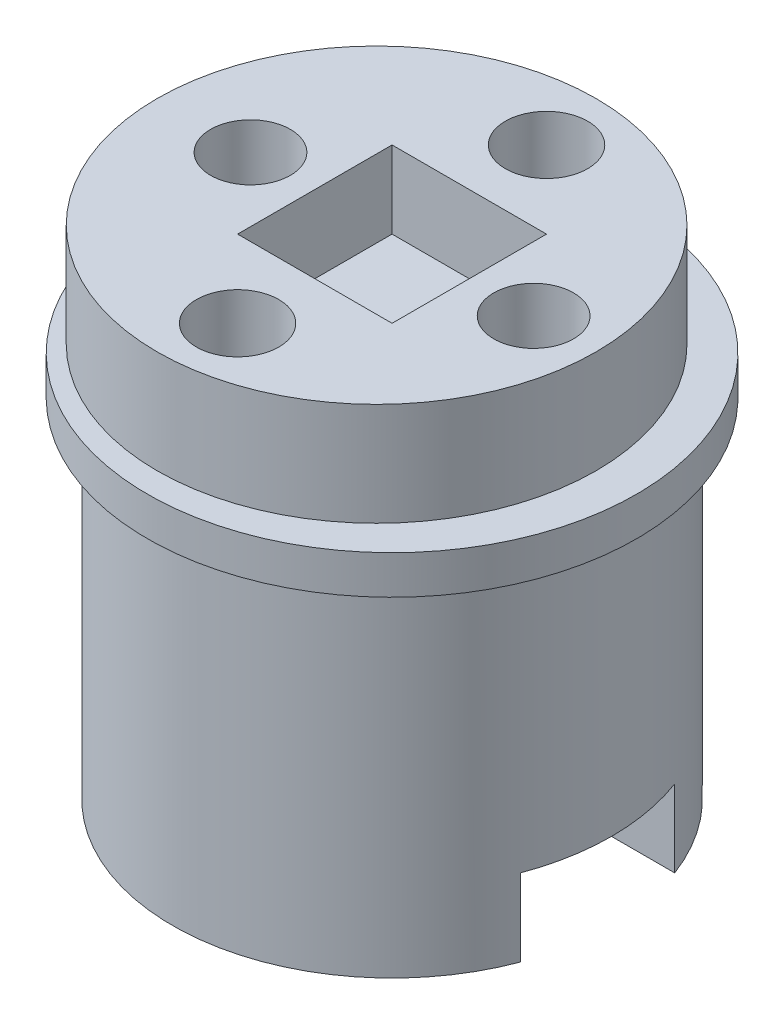
SolidWorks part; units mm, degrees
material "Like ABS"
ref_plane "Front Plane" through (0, 0, 0) normal (0, 0, 1) x (1, 0, 0)
ref_plane "Top Plane" through (0, 0, 0) normal (0, 1, 0) x (1, 0, 0)
ref_plane "Right Plane" through (0, 0, 0) normal (1, 0, 0) x (0, 0, -1)
sketch "Sketch1" plane through (0, 0, 0) normal (0, 1, 0) x (1, 0, 0)
  circle A0 centre (0, 0) radius 8.525
  dimension "D1" = 17.05
extrude "Boss-Extrude11" add sketch "Sketch1" along normal blind 4
sketch "Sketch20" plane through (0, 4, 0) normal (0, 1, 0) x (1, 0, 0)
  line L0 (0, 0) -> (1.2, 0) construction
  circle A0 centre (1.2, 0) radius 8.575
  dimension "D2" = 17.15
  dimension "D1" = 1.2
extrude "Boss-Extrude12" add sketch "Sketch20" along normal blind 4
sketch "Sketch21" plane through (0, 8, 0) normal (0, 1, 0) x (1, 0, 0)
  line L0 (0, 0) -> (0.6, 0) construction
  circle A0 centre (0.6, 0) radius 9.5
  dimension "D2" = 19
  dimension "D1" = 0.6
extrude "Boss-Extrude13" add sketch "Sketch21" along normal blind 1.25
sketch "Sketch22" plane through (0, 9.25, 0) normal (0, 1, 0) x (1, 0, 0)
  line L0 (0, 0) -> (0.6, 0) construction
  circle A0 centre (0.6, 0) radius 8.55
  dimension "D2" = 17.1
  dimension "D1" = 0.6
extrude "Boss-Extrude14" add sketch "Sketch22" along normal blind 7
sketch "Sketch30" plane through (0, 0, 0) normal (0, -1, 0) x (1, 0, 0)
  line L0 (0, 0) -> (0.6, 0) construction
  circle A1 centre (0.6, 0) radius 8.525
  dimension "D1" = 0.6
  dimension "D2" = 17.05
extrude "Boss-Extrude15" add sketch "Sketch30" along normal blind 15
sketch "Sketch33" plane through (0, -15, 0) normal (0, -1, 0) x (1, 0, 0)
  line L0 (0, 0) -> (0.6, 0) construction
  circle A0 centre (0.6, 0) radius 2.1
  dimension "D2" = 4.2
  dimension "D1" = 0.6
extrude "Cut-Extrude14" cut sketch "Sketch33" against normal blind 5.8
sketch "Sketch35" plane through (0, 0, 0) normal (0, -1, 0) x (1, 0, 0)
  line L0 (0, 0) -> (0.6, 0) construction
  circle A0 centre (0.6, 0) radius 9.5
  dimension "D2" = 19
  dimension "D1" = 0.6
extrude "Boss-Extrude16" add sketch "Sketch35" along normal blind 1.5
sketch "Sketch36" plane through (0, -15, 0) normal (0, -1, 0) x (1, 0, 0)
  circle A0 centre (0.6, 0) radius 6 construction
  circle A1 centre (0.6, 6) radius 1.6
  dimension "D1" = 12
  dimension "D2" = 3.2
extrude "Cut-Extrude15" cut sketch "Sketch36" against normal up to surface (31.25 mm away) up to face at (0.6, 16.25, 8.55)
pattern_circular "CirPattern1" count 2 over 360 about axis through (0.6, 0, 0) along (0, 1, 0) of "Cut-Extrude15"
sketch "Sketch43" plane through (0, -15, 0) normal (0, -1, 0) x (1, 0, 0)
  circle A1 centre (-4.9, 0) radius 1.55
  circle A2 centre (6.1, 0) radius 1.55
  circle A3 centre (0.6, 0) radius 5.5 construction
  dimension "D1" = 11
  dimension "D2" = 3.1
extrude "Cut-Extrude20" cut sketch "Sketch43" against normal up to surface (31.25 mm away) up to face at (0.6, 16.25, -4.4)
sketch "Sketch44" plane through (0, 16.25, 0) normal (0, 1, 0) x (1, 0, 0)
  circle A0 centre (-4.9, 0) radius 2
  circle A1 centre (6.1, 0) radius 2
  dimension "D1" = 4
extrude "Cut-Extrude21" cut sketch "Sketch44" against normal blind 4
sketch "Sketch45" plane through (0, 16.25, 0) normal (0, 1, 0) x (1, 0, 0)
  line L2 (-2.4, -6) -> (-2.4, -10.8726)
  line L3 (-2.4, -10.8726) -> (3.6, -10.8726)
  line L4 (3.6, -6) -> (3.6, -10.8726)
  line L6 (-2.4, 6) -> (-2.4, 11.4221)
  line L7 (-2.4, 11.4221) -> (3.6, 11.4221)
  line L8 (3.6, 6) -> (3.6, 11.4221)
  arc A0 (-2.4, 6) -> (3.6, 6) centre (0.6, 6) ccw
  arc A1 (3.6, -6) -> (-2.4, -6) centre (0.6, -6) ccw
  dimension "D1" = 6
  dimension "D2" = 6
extrude "Cut-Extrude22" cut sketch "Sketch45" against normal blind 3
sketch "Sketch46" plane through (0, -15, 0) normal (0, -1, 0) x (1, 0, 0)
  line L1 (-4.9, 3) -> (-9.7199, 3)
  line L3 (-4.9, -3) -> (-9.7199, -3)
  line L4 (-9.7199, 3) -> (-9.7199, -3)
  line L5 (6.1, 3) -> (10.8894, 3)
  line L7 (6.1, -3) -> (10.8894, -3)
  line L8 (10.8894, 3) -> (10.8894, -3)
  arc A0 (-4.9, -3) -> (-4.9, 3) centre (-4.9, 0) ccw
  arc A1 (6.1, 3) -> (6.1, -3) centre (6.1, 0) ccw
  dimension "D1" = 6
extrude "Cut-Extrude23" cut sketch "Sketch46" against normal blind 3
sketch "Sketch47" plane through (0, 16.25, 0) normal (0, 1, 0) x (1, 0, 0)
  line L1 (-10.7961, 10.8817) -> (11.5477, 10.8817)
  line L2 (-10.7961, 10.8817) -> (-10.7961, -10.9081)
  line L3 (-10.7961, -10.9081) -> (11.5477, -10.9081)
  line L4 (11.5477, 10.8817) -> (11.5477, -10.9081)
extrude "Cut-Extrude24" cut sketch "Sketch47" against normal up to surface (12.25 mm away) up to face at (-7.95, 4, 0)
sketch "Sketch48" plane through (0, 4, 0) normal (0, 1, 0) x (1, 0, 0)
  line L1 (3.6, 3) -> (-2.4, 3)
  line L2 (3.6, 3) -> (3.6, -3)
  line L3 (3.6, -3) -> (-2.4, -3)
  line L4 (-2.4, 3) -> (-2.4, -3)
  circle A0 centre (0.6, 0) radius 3 construction
  dimension "D1" = 6
extrude "Cut-Extrude25" cut sketch "Sketch48" against normal blind 3
